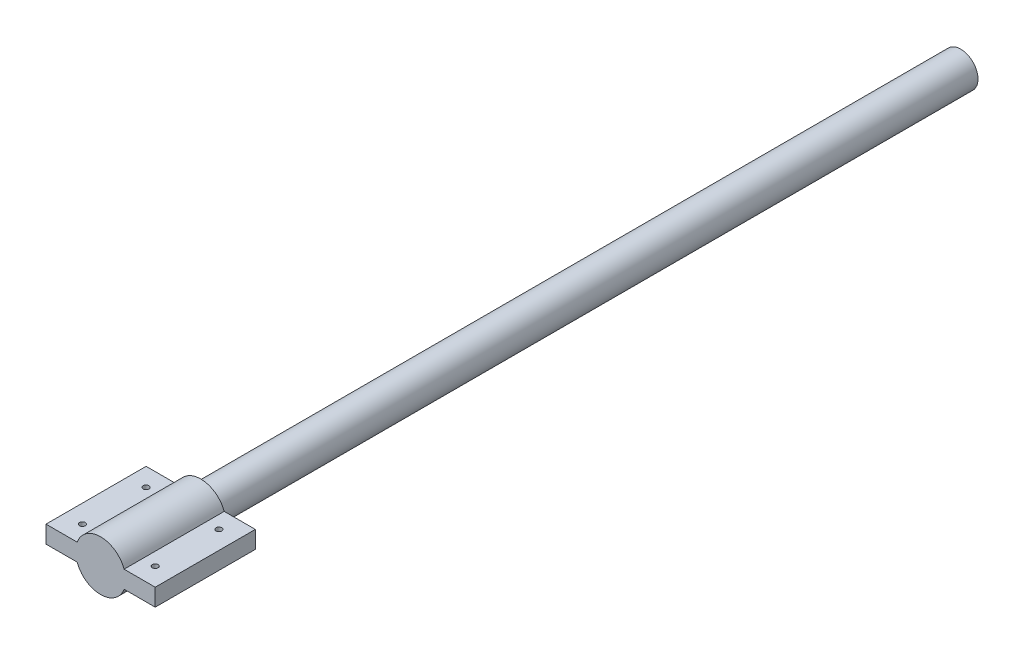
SolidWorks part; units mm, degrees
ref_plane "Front Plane" through (0, 0, 0) normal (0, 0, 1) x (1, 0, 0)
ref_plane "Top Plane" through (0, 0, 0) normal (0, 1, 0) x (1, 0, 0)
ref_plane "Right Plane" through (0, 0, 0) normal (1, 0, 0) x (0, 0, -1)
sketch "Sketch1" plane through (0, 0, 0) normal (0, 0, 1) x (1, 0, 0)
  circle A0 centre (0, 0) radius 19
  dimension "D1" = 38
extrude "Boss-Extrude1" add sketch "Sketch1" along normal blind 945
sketch "Sketch2" plane through (0, 0, 945) normal (0, 0, 1) x (1, 0, 0)
  line L0 (-25.7978, -9.525) -> (-60, -9.525)
  line L1 (-60, -9.525) -> (-60, 9.525)
  line L2 (-60, 9.525) -> (-25.7978, 9.525)
  line L3 (0, 19) -> (0, -19) construction
  line L4 (25.7978, -9.525) -> (60, -9.525)
  line L5 (60, 9.525) -> (25.7978, 9.525)
  line L6 (60, -9.525) -> (60, 9.525)
  line L7 (-25.7978, 9.525) -> (-60, 9.525)
  line L8 (-60, -9.525) -> (-25.7978, -9.525)
  line L9 (25.7978, 9.525) -> (60, 9.525)
  line L10 (60, -9.525) -> (25.7978, -9.525)
  circle A0 centre (0, 0) radius 27.5
  circle A1 centre (0, 0) radius 19 construction
  circle A2 centre (0, 0) radius 19
  point P13 (-60, 0)
  circle M8 centre (0, 0) radius 19
  dimension "D1" = 55
  dimension "D2" = 19.05
  dimension "D3" = 120
extrude "Boss-Extrude2" add sketch "Sketch2" against normal blind 110 contours A0 L2 L1 L0 | A0 L4 L6 L5 | L3 M8 | A2 L3
sketch "Sketch3" plane through (0, 9.525, 0) normal (0, 1, 0) x (1, 0, 0)
  line L0 (-25.7978, -945) -> (25.7978, -945) construction
  line L1 (-40, -855) -> (40, -855) construction
  line L2 (-40, -855) -> (-40, -925) construction
  line L3 (-40, -925) -> (40, -925) construction
  line L4 (40, -855) -> (40, -925) construction
  line L5 (-40, -855) -> (40, -925) construction
  line L6 (-40, -925) -> (40, -855) construction
  line L7 (-25.7978, -945) -> (25.7978, -945)
  line L8 (-60, -835) -> (-60, -945) construction
  line L9 (-60, -835) -> (-60, -945)
  circle A0 centre (-40, -855) radius 3.175
  circle A1 centre (40, -855) radius 3.175
  circle A2 centre (40, -925) radius 3.175
  circle A3 centre (-40, -925) radius 3.175
  point P0 (0, -890)
  point P13 (0, 0)
  point P14 (-60, -890)
  point P15 (0, 0)
  point P16 (0, -945)
  dimension "D3" = 6.35
  dimension "D4" = 6.35
  dimension "D5" = 6.35
  dimension "D6" = 6.35
  dimension "D1" = 80
  dimension "D2" = 70
extrude "Cut-Extrude1" cut sketch "Sketch3" against normal through all contours A2 | A1 | A3 | A0
